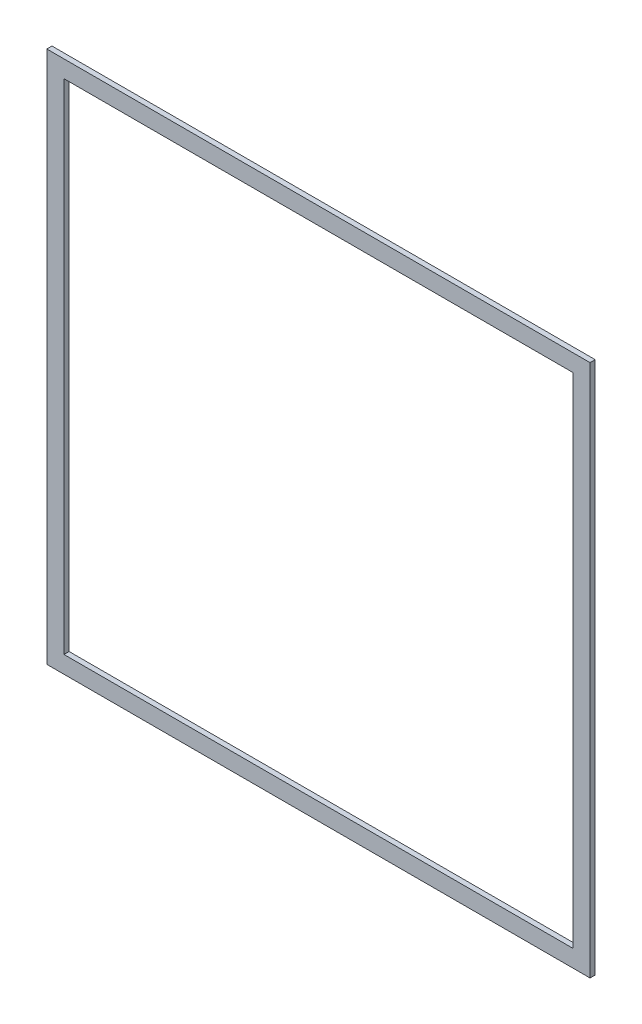
SolidWorks part; units mm, degrees
ref_plane "Front Plane" through (0, 0, 0) normal (0, 0, 1) x (1, 0, 0)
ref_plane "Top Plane" through (0, 0, 0) normal (0, 1, 0) x (1, 0, 0)
ref_plane "Right Plane" through (0, 0, 0) normal (1, 0, 0) x (0, 0, -1)
sketch "Sketch1" plane through (0, 0, 0) normal (0, 0, 1) x (1, 0, 0)
  line L0 (0, 0) -> (0, 310.8)
  line L1 (0, 310.8) -> (316.8, 310.8)
  line L2 (316.8, 310.8) -> (316.8, 0)
  line L3 (316.8, 0) -> (314.3376, 0)
  line L4 (306.8, 10) -> (306.8, 300.8)
  line L5 (306.8, 300.8) -> (10, 300.8)
  line L6 (10, 300.8) -> (10, 10)
  line L7 (10, 0) -> (0, 0)
  line L8 (10, 0) -> (314.3376, 0)
  line L9 (10, 10) -> (306.8, 10)
  point P6 (0, 0)
  point P8 (257.8968, 26.0351)
  point P12 (314.8, 23.953)
  point P14 (317.8702, 10)
  dimension "D1" = 10
  dimension "D2" = 10
  dimension "D3" = 10
  dimension "D4" = 316.8
  dimension "D5" = 310.8
  dimension "D6" = 10
  dimension "D7" = 10
extrude "Boss-Extrude1" add sketch "Sketch1" along normal blind 3
